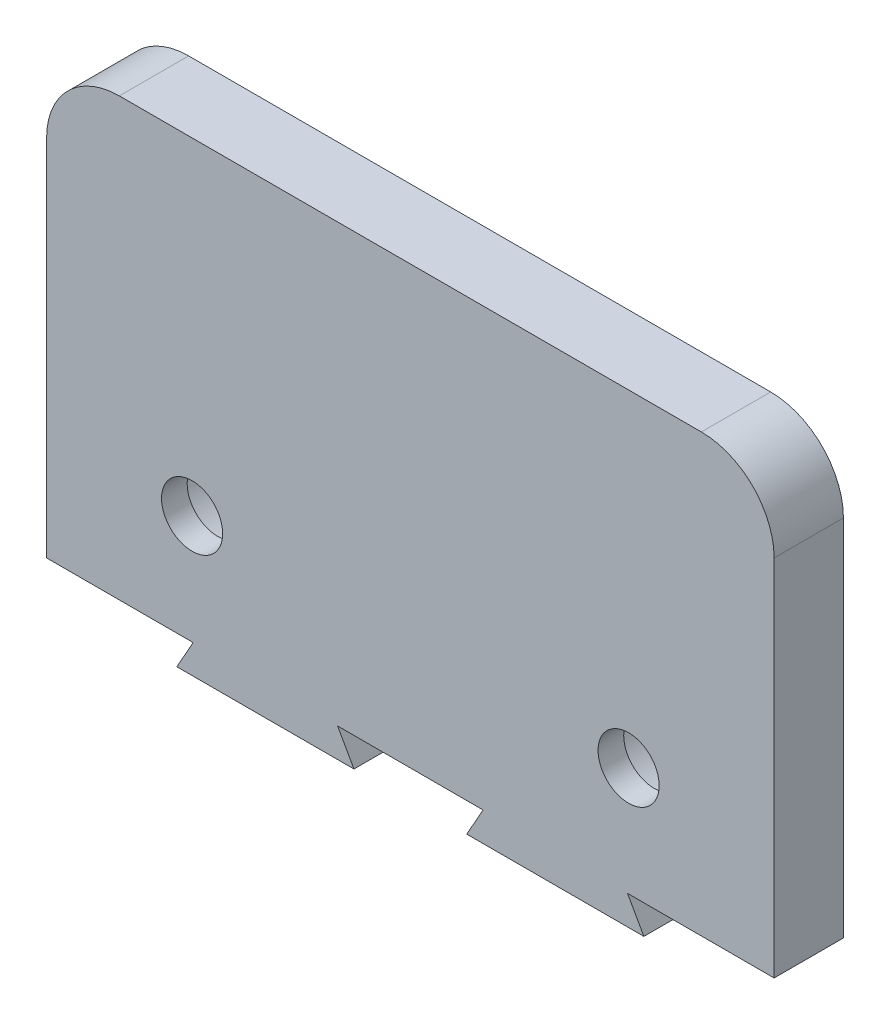
SolidWorks part; units mm, degrees
material "Liga 1060"
ref_plane "Plano frontal" through (0, 0, 0) normal (0, 0, 1) x (1, 0, 0)
ref_plane "Plano superior" through (0, 0, 0) normal (0, 1, 0) x (1, 0, 0)
ref_plane "Plano direito" through (0, 0, 0) normal (1, 0, 0) x (0, 0, -1)
sketch "Esboço1" plane through (0, 0, 0) normal (0, 1, 0) x (1, 0, 0)
  line L1 (50, -4.7625) -> (-50, -4.7625)
  line L2 (50, -4.7625) -> (50, 4.7625)
  line L3 (50, 4.7625) -> (-50, 4.7625)
  line L4 (-50, -4.7625) -> (-50, 4.7625)
  line L5 (50, -4.7625) -> (-50, 4.7625) construction
  line L6 (50, 4.7625) -> (-50, -4.7625) construction
  point P0 (0, 0)
  dimension "D1" = 100
  dimension "D2" = 9.525
extrude "Ressalto-extrusão1" add sketch "Esboço1" along normal blind 60
sketch "Esboço2" plane through (0, 0, 0) normal (0, 0, 1) x (1, 0, 0)
  line L0 (-29.85, 0) -> (-10, 0)
  line L1 (-50, 0) -> (50, 0) construction
  line L2 (-10, 0) -> (-7.75, -4)
  line L3 (-7.75, -4) -> (-32.1, -4)
  line L4 (-32.1, -4) -> (-29.85, 0)
  dimension "D1" = 19.85
  dimension "D2" = 24.35
  dimension "D3" = 4
  dimension "D4" = 10
extrude "Ressalto-extrusão2" add sketch "Esboço2" along normal through all and the other way through all
mirror "Espelhar1" about plane through (0, 0, 0) normal (1, 0, 0) of "Ressalto-extrusão2"
fillet "Filete1" radius 10 2 edges at (50, 60, 0) (-50, 60, 0)
sketch "Esboço3" plane through (0, 0, 4.7625) normal (0, 0, 1) x (1, 0, 0)
  line L0 (50, 15) -> (-50, 15) construction
  line L1 (-50, 50) -> (-50, 0) construction
  line L2 (50, 50) -> (50, 0) construction
  circle A0 centre (-30, 15) radius 4
  circle A1 centre (30, 15) radius 4
  point P5 (0, 15)
  dimension "D2" = 30
  dimension "D4" = 8
  dimension "D1" = 15
  dimension "D3" = 30
extrude "Corte-extrusão1" cut sketch "Esboço3" against normal through all
hole_wizard "Rebaixo para parafuso com cabeça panela de M82" positions "Esboço8" profile "Esboço9" counterbore size "M8" standard "ISO"
sketch "Esboço8" plane through (0, 0, -4.7625) normal (0, 0, -1) x (-1, 0, 0)
  point P0 (-30, 15)
  point P3 (30, 15)
sketch "Esboço9" plane through (30, 15, -4.7625) normal (1, 0, 0) x (0, 1, 0)
  line L0 (0, 0) -> (0, 22.5736)
  line L1 (0, 22.5736) -> (4.2, 20.05)
  line L2 (4.2, 20.05) -> (4.2, 6)
  line L3 (4.2, 6) -> (9, 6)
  line L5 (9, 6) -> (9, 0.025)
  line L6 (9, 0.025) -> (9.025, 0)
  line L7 (9.025, 0) -> (0, 0)
  line L8 (-9, 0.025) -> (-9.025, 0) construction
  line L10 (0, 22.5736) -> (-4.2, 20.05) construction
  line L11 (0, -6.35) -> (0, 107.95) construction
  dimension "Hole Dia." = 8.4
  dimension "Hole Depth" = 20.05
  dimension "C'Bore Dia." = 18
  dimension "C'Bore Depth" = 6
  dimension "Near C'Sink Dia." = 18.05
  dimension "Near C'Sink Angle" = 90
  dimension "Drill Angle" = 118
